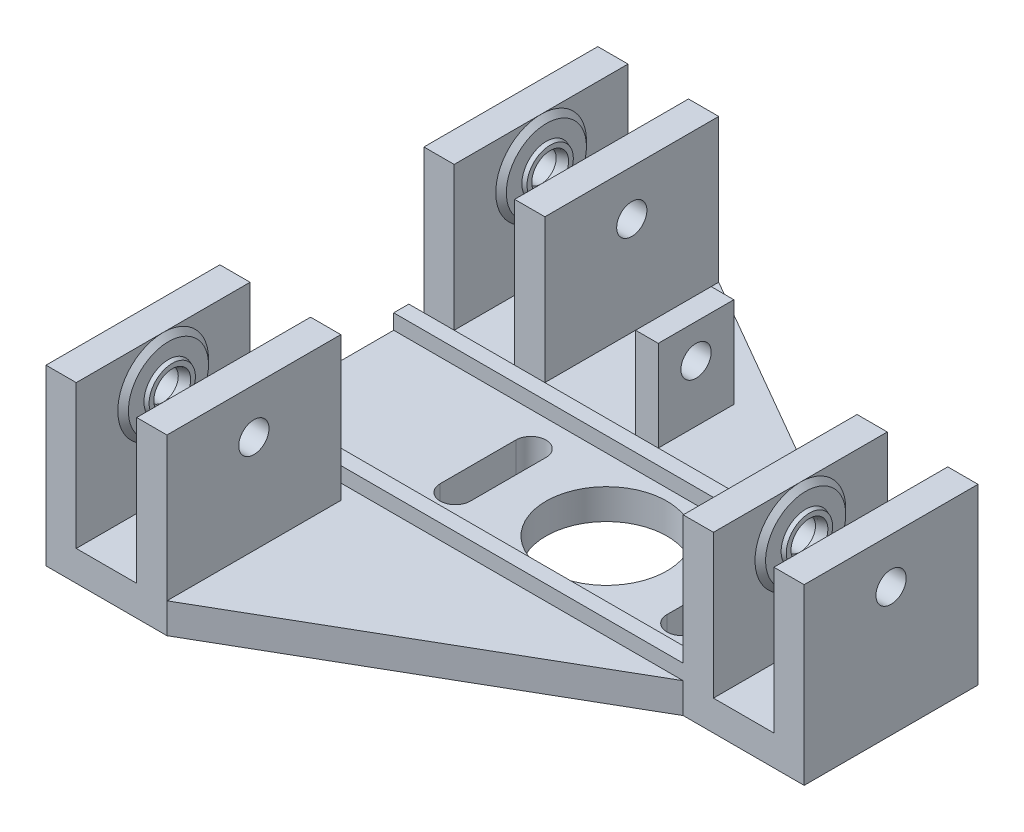
SolidWorks part; units mm, degrees
ref_plane "Front Plane" through (0, 0, 0) normal (0, 0, 1) x (1, 0, 0)
ref_plane "Top Plane" through (0, 0, 0) normal (0, 1, 0) x (1, 0, 0)
ref_plane "Right Plane" through (0, 0, 0) normal (1, 0, 0) x (0, 0, -1)
sketch "Sketch1" plane through (0, 0, 0) normal (0, 1, 0) x (1, 0, 0)
  line L8 (-37.6506, 36.5) -> (-21.6506, 36.5) construction
  line L10 (-37.6506, 45.7376) -> (-37.6506, -45.7376)
  line L11 (-37.6506, -45.7376) -> (41.5692, 0)
  line L12 (41.5692, 0) -> (-37.6506, 45.7376)
  line L18 (-37.6506, -36.5) -> (-21.6506, -36.5) construction
  line L19 (21.6506, 11.5) -> (21.6506, -11.5) construction
  line L20 (21.6506, 11.5) -> (37.6506, 11.5)
  line L21 (37.6506, 11.5) -> (37.6506, -11.5)
  line L22 (37.6506, -11.5) -> (21.6506, -11.5)
  line L23 (-21.6506, -36.5) -> (-21.6506, 36.5) construction
  line L24 (21.6506, 0) -> (-21.6506, 0) construction
  line L25 (-37.6506, 36.5) -> (-21.6506, 36.5)
  line L26 (-37.6506, -36.5) -> (-21.6506, -36.5)
  line L27 (15, -5) -> (15, 5) construction
  line L28 (13, -5) -> (13, 5)
  line L29 (17, -5) -> (17, 5)
  line L30 (-15, -5) -> (-15, 5) construction
  line L31 (-17, -5) -> (-17, 5)
  line L32 (-13, -5) -> (-13, 5)
  circle A0 centre (0, 0) radius 8
  arc A1 (13, -5) -> (17, -5) centre (15, -5) ccw
  arc A2 (17, 5) -> (13, 5) centre (15, 5) ccw
  arc A3 (-17, -5) -> (-13, -5) centre (-15, -5) ccw
  arc A4 (-13, 5) -> (-17, 5) centre (-15, 5) ccw
  point P9 (0, 0)
  point P15 (15, 0)
  point P26 (-15, 0)
  dimension "D1" = 16
  dimension "D12" = 16
  dimension "D2" = 16
  dimension "D3" = 50
  dimension "D4" = 2
  dimension "D5" = 23
  dimension "D6" = 2
  dimension "D7" = 16
  dimension "D8" = 10
  dimension "D9" = 10
  dimension "D10" = 15
  dimension "D11" = 15
extrude "Boss-Extrude1" add sketch "Sketch1" along normal blind 4 contours L10 L26 L11 L21 L12 L25 A0 | L22 L21 L11 | L21 L20 L12
sketch "Sketch2" plane through (0, 4, 0) normal (0, 1, 0) x (1, 0, 0)
  line L0 (37.6506, -11.5) -> (21.6506, -11.5) construction
  line L1 (37.6506, 11.5) -> (33.6506, 11.5)
  line L2 (37.6506, 11.5) -> (37.6506, -11.5)
  line L3 (37.6506, -11.5) -> (33.6506, -11.5)
  line L4 (33.6506, 11.5) -> (33.6506, -11.5)
  line L5 (-37.6506, 36.5) -> (-37.6506, -36.5) construction
  line L6 (21.6506, 11.5) -> (25.6506, 11.5)
  line L7 (21.6506, 11.5) -> (21.6506, -11.5)
  line L8 (21.6506, -11.5) -> (25.6506, -11.5)
  line L9 (25.6506, 11.5) -> (25.6506, -11.5)
  line L10 (-37.6506, 36.5) -> (-33.6506, 36.5)
  line L11 (-37.6506, 36.5) -> (-37.6506, 13.5)
  line L12 (-37.6506, 13.5) -> (-33.6506, 13.5)
  line L13 (-33.6506, 36.5) -> (-33.6506, 13.5)
  line L14 (-21.6506, 36.5) -> (-25.6506, 36.5)
  line L15 (-21.6506, 36.5) -> (-21.6506, 13.5)
  line L16 (-21.6506, 13.5) -> (-25.6506, 13.5)
  line L17 (-25.6506, 36.5) -> (-25.6506, 13.5)
  line L18 (-37.6506, -36.5) -> (-33.6506, -36.5)
  line L19 (-37.6506, -36.5) -> (-37.6506, -13.5)
  line L20 (-37.6506, -13.5) -> (-33.6506, -13.5)
  line L21 (-33.6506, -36.5) -> (-33.6506, -13.5)
  line L23 (-21.6506, -36.5) -> (-25.6506, -36.5)
  line L24 (-21.6506, -36.5) -> (-21.6506, -13.5)
  line L25 (-21.6506, -13.5) -> (-25.6506, -13.5)
  line L26 (-25.6506, -36.5) -> (-25.6506, -13.5)
  dimension "D1" = 23
  dimension "D2" = 23
  dimension "D3" = 23
  dimension "D4" = 23
  dimension "D5" = 4
  dimension "D6" = 4
  dimension "D7" = 4
  dimension "D8" = 4
  dimension "D9" = 4
  dimension "D10" = 4
extrude "Boss-Extrude2" add sketch "Sketch2" along normal blind 19
sketch "Sketch3" plane through (-37.6506, 0, 0) normal (-1, 0, 0) x (0, 0, 1)
  line L0 (-36.5, 17) -> (-13.5, 17) construction
  line L1 (-36.5, 23) -> (-36.5, 0) construction
  line L2 (-13.5, 23) -> (-13.5, 4) construction
  line L3 (-11.5, 17) -> (11.5, 17) construction
  line L4 (-11.5, 23) -> (-11.5, 4) construction
  line L5 (11.5, 23) -> (11.5, 4) construction
  line L6 (13.5, 17) -> (36.5, 17) construction
  line L7 (13.5, 23) -> (13.5, 4) construction
  line L8 (36.5, 23) -> (36.5, 0) construction
  line L9 (-36.5, 23) -> (-13.5, 23) construction
  line L10 (-11.5, 23) -> (11.5, 23) construction
  circle A0 centre (-25, 17) radius 2
  circle A1 centre (0, 17) radius 2
  circle A2 centre (25, 17) radius 2
  dimension "D3" = 4
  dimension "D4" = 4
  dimension "D5" = 4
  dimension "D1" = 6
  dimension "D2" = 6
extrude "Cut-Extrude1" cut sketch "Sketch3" against normal through all
sketch "Sketch4" plane through (-25.6506, 0, 0) normal (-1, 0, 0) x (0, 0, 1)
  circle A0 centre (-25, 17) radius 2
  circle A1 centre (-25, 17) radius 6
  circle A2 centre (25, 17) radius 6
  circle A3 centre (25, 17) radius 2
  dimension "D1" = 12
  dimension "D2" = 12
extrude "Boss-Extrude3" add sketch "Sketch4" along normal blind 0.7 draft 45
sketch "Sketch5" plane through (-25.6506, 0, 0) normal (-1, 0, 0) x (0, 0, 1)
  circle A0 centre (-25, 17) radius 2
  circle A1 centre (-25, 17) radius 3.5
  circle A5 centre (25, 17) radius 2
  circle A6 centre (25, 17) radius 3.5
  dimension "D1" = 7
  dimension "D2" = 7
extrude "Boss-Extrude4" add sketch "Sketch5" along normal blind 1.2 draft 20
sketch "Sketch6" plane through (-33.6506, 0, 0) normal (1, 0, 0) x (0, 0, -1)
  circle A0 centre (-25, 17) radius 6
  circle A1 centre (25, 17) radius 6
  circle A2 centre (-25, 17) radius 2
  circle A3 centre (25, 17) radius 2
  dimension "D1" = 12
  dimension "D2" = 12
extrude "Boss-Extrude5" add sketch "Sketch6" along normal blind 0.7 draft 45
sketch "Sketch7" plane through (-33.6506, 0, 0) normal (1, 0, 0) x (0, 0, -1)
  circle A0 centre (-25, 17) radius 2
  circle A1 centre (-25, 17) radius 3.5
  circle A2 centre (25, 17) radius 2
  circle A3 centre (25, 17) radius 3.5
  dimension "D1" = 7
  dimension "D2" = 7
extrude "Boss-Extrude6" add sketch "Sketch7" along normal blind 1.2 draft 20
sketch "Sketch8" plane through (25.6506, 0, 0) normal (1, 0, 0) x (0, 0, -1)
  circle A0 centre (0, 17) radius 2
  circle A1 centre (0, 17) radius 6
  dimension "D1" = 12
extrude "Boss-Extrude7" add sketch "Sketch8" along normal blind 0.7 draft 45
sketch "Sketch9" plane through (25.6506, 0, 0) normal (1, 0, 0) x (0, 0, -1)
  circle A0 centre (0, 17) radius 2
  circle A1 centre (0, 17) radius 3.5
  dimension "D1" = 7
extrude "Boss-Extrude8" add sketch "Sketch9" along normal blind 1.2 draft 20
sketch "Sketch11" plane through (33.6506, 0, 0) normal (-1, 0, 0) x (0, 0, 1)
  circle A0 centre (0, 17) radius 2
  circle A1 centre (0, 17) radius 6
  dimension "D1" = 12
extrude "Boss-Extrude9" add sketch "Sketch11" along normal blind 0.7 draft 45
sketch "Sketch12" plane through (33.6506, 0, 0) normal (-1, 0, 0) x (0, 0, 1)
  circle A0 centre (0, 17) radius 2
  circle A1 centre (0, 17) radius 3.5
  dimension "D1" = 7
extrude "Boss-Extrude10" add sketch "Sketch12" along normal blind 1.2 draft 20
sketch "Sketch13" plane through (0, 4, 0) normal (0, 1, 0) x (1, 0, 0)
  line L0 (-37.6506, 13.5) -> (-37.6506, -13.5) construction
  line L1 (21.6506, 11.5) -> (-37.6506, 11.5)
  line L2 (21.6506, 11.5) -> (21.6506, 9.5)
  line L3 (21.6506, 9.5) -> (-37.6506, 9.5)
  line L4 (-37.6506, 11.5) -> (-37.6506, 9.5)
  line L6 (21.6506, -11.5) -> (-37.6506, -11.5)
  line L7 (21.6506, -11.5) -> (21.6506, -9.5)
  line L8 (21.6506, -9.5) -> (-37.6506, -9.5)
  line L9 (-37.6506, -11.5) -> (-37.6506, -9.5)
  dimension "D1" = 2
  dimension "D2" = 2
extrude "Boss-Extrude11" add sketch "Sketch13" along normal blind 2
sketch "Sketch14" plane through (0, 4, 0) normal (0, 1, 0) x (1, 0, 0)
  line L0 (-21.6506, 13.5) -> (-21.6506, 36.5) construction
  line L1 (-9.6506, 13.5) -> (-6.6506, 13.5)
  line L2 (-9.6506, 13.5) -> (-9.6506, 23.5)
  line L3 (-9.6506, 23.5) -> (-6.6506, 23.5)
  line L4 (-6.6506, 13.5) -> (-6.6506, 23.5)
  line L5 (21.6506, 11.5) -> (-37.6506, 11.5) construction
  dimension "D1" = 12
  dimension "D2" = 3
  dimension "D3" = 10
  dimension "D4" = 2
extrude "Boss-Extrude12" add sketch "Sketch14" along normal blind 12
sketch "Sketch15" plane through (-6.6506, 0, 0) normal (1, 0, 0) x (0, 0, -1)
  line L0 (13.5, 16) -> (23.5, 16) construction
  line L1 (13.5, 16) -> (13.5, 4) construction
  circle A0 centre (18.5, 11.5) radius 2
  dimension "D1" = 4
  dimension "D2" = 4.5
  dimension "D3" = 5
extrude "Cut-Extrude2" cut sketch "Sketch15" against normal up to next
